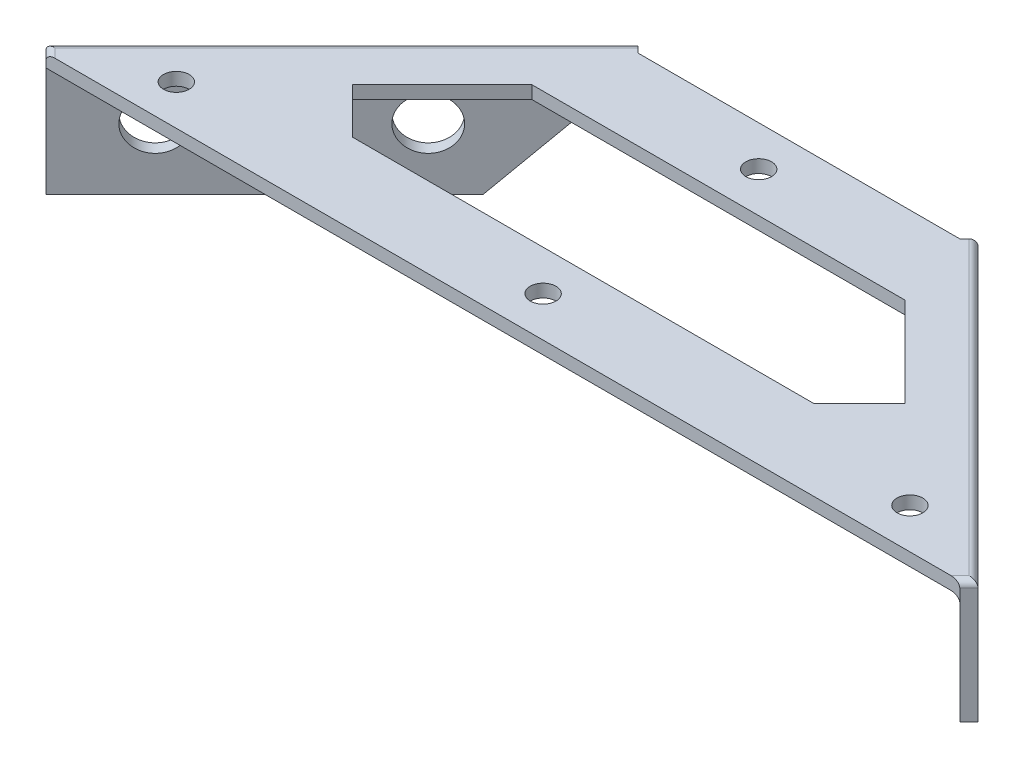
SolidWorks part; units mm, degrees
material "1060 Alloy"
ref_plane "Front Plane" through (0, 0, 0) normal (0, 0, 1) x (1, 0, 0)
ref_plane "Top Plane" through (0, 0, 0) normal (0, 1, 0) x (1, 0, 0)
ref_plane "Right Plane" through (0, 0, 0) normal (1, 0, 0) x (0, 0, -1)
sketch "Sketch1" plane through (0, 0, 0) normal (0, 1, 0) x (1, 0, 0)
  line L0 (0, 0) -> (0, 46) construction
  line L1 (25, 46) -> (-25, 46)
  line L2 (-25, 46) -> (-71, 0)
  line L3 (-71, 0) -> (71, 0)
  line L4 (25, 46) -> (71, 0)
  dimension "D1" = 46
  dimension "D2" = 71
  dimension "D3" = 45
extrude "Boss-Extrude1" add sketch "Sketch1" along normal blind 2
sketch "Sketch2" plane through (0, 0, 0) normal (0, -1, 0) x (-1, 0, 0)
  line L0 (25, 46) -> (71, 0)
  line L1 (25, 46) -> (26.4142, 47.4142)
  line L2 (71, 0) -> (72.4142, 1.4142)
  line L3 (26.4142, 47.4142) -> (72.4142, 1.4142)
  line L4 (0, 46) -> (0, 0) construction
  line L5 (-25, 46) -> (25, 46) construction
  line L6 (-26.4142, 47.4142) -> (-72.4142, 1.4142)
  line L7 (-71, 0) -> (-72.4142, 1.4142)
  line L8 (-25, 46) -> (-26.4142, 47.4142)
  line L9 (-25, 46) -> (-71, 0)
  dimension "D1" = 2
extrude "Boss-Extrude2" add sketch "Sketch2" along normal blind 17 and the other way up to surface other way up to face at (0, 2, -23)
sketch "Sketch7" plane through (-36.9142, 0, -36.9142) normal (-0.7071, 0, -0.7071) x (-0.7071, 0, 0.7071)
  line L0 (50.2046, -7.5) -> (-14.8492, -7.5) construction
  line L1 (50.2046, 2) -> (50.2046, -17) construction
  line L2 (-14.8492, 2) -> (-14.8492, -17) construction
  circle A0 centre (38.2046, -7.5) radius 4
  circle A1 centre (8.2046, -7.5) radius 4
  dimension "D1" = 8
  dimension "D2" = 30
  dimension "D3" = 12
extrude "Cut-Extrude4" cut sketch "Sketch7" against normal through all
fillet "Fillet1" radius 1 5 edges at (71.7071, 2, -0.7071) (-71.7071, 2, -0.7071) (-49.4142, 2, -24.4142) (48, 0, -23) (49.4142, 2, -24.4142)
sketch "Sketch3" plane through (-35.5, 0, -35.5) normal (0.7071, 0, 0.7071) x (0.7071, 0, -0.7071)
  line L0 (14.8492, 0) -> (-2.1508, -17)
  line L1 (14.8492, -17) -> (-50.2046, -17) construction
  line L2 (-2.1508, -17) -> (14.8492, -17)
  line L3 (14.8492, -17) -> (14.8492, 0)
  dimension "D1" = 45
extrude "Cut-Extrude1" cut sketch "Sketch3" against normal through all
ref_plane "Plane1" through (0, 0, 0) normal (-1, 0, 0) x (0, 0, 1)
sketch "Sketch4" plane through (0, 0, 0) normal (0, -1, 0) x (-1, 0, 0)
  line L0 (0, 46.3421) -> (0, 0) construction
  line L1 (0, -9.9) -> (0, 9.9) construction
  line L3 (29.0147, 33.5) -> (-29.0147, 33.5)
  line L4 (0, 33.5) -> (0, 12.5)
  line L5 (-35.8726, 12.5) -> (35.8726, 12.5)
  line L7 (71, 0) -> (-69.5858, 0) construction
  line L8 (35.8726, 12.5) -> (42.9437, 19.5711)
  line L9 (42.9437, 19.5711) -> (29.0147, 33.5)
  line L10 (25, 46) -> (71, 0) construction
  line L11 (37.0208, 33.9792) -> (71, 0) construction
  line L12 (-42.9437, 19.5711) -> (-29.0147, 33.5)
  line L13 (-35.8726, 12.5) -> (-42.9437, 19.5711)
  dimension "D1" = 12.5
  dimension "D2" = 21
  dimension "D3" = 135
  dimension "D4" = 6
  dimension "D5" = 10
extrude "Cut-Extrude2" cut sketch "Sketch4" against normal through all contours L8 L9 L3 L4 L5 | L13 L5 L4 L3 L12
mirror "Mirror1" about plane through (0, 0, 0) normal (-1, 0, 0) of "Cut-Extrude4", "Cut-Extrude1"
sketch "Sketch5" plane through (0, 0, 0) normal (0, -1, 0) x (-1, 0, 0)
  line L0 (0, 0) -> (0, 12.5) construction
  line L1 (0, -9.9) -> (0, 9.9) construction
  line L2 (-35.8726, 12.5) -> (35.8726, 12.5) construction
  line L3 (0, 33.5) -> (0, 46) construction
  line L4 (29.0147, 33.5) -> (-29.0147, 33.5) construction
  line L5 (-23.5858, 46) -> (25, 46) construction
  line L6 (0, 6.25) -> (-63.3358, 6.25) construction
  line L7 (-23.5858, 46) -> (-69.5858, 0) construction
  circle A0 centre (0, 6.25) radius 2
  circle A1 centre (0, 39.75) radius 2
  circle A2 centre (-57, 6.25) radius 2
  circle A3 centre (57, 6.25) radius 2
  dimension "D1" = 4
  dimension "D2" = 4
  dimension "D3" = 57
extrude "Cut-Extrude3" cut sketch "Sketch5" against normal through all
